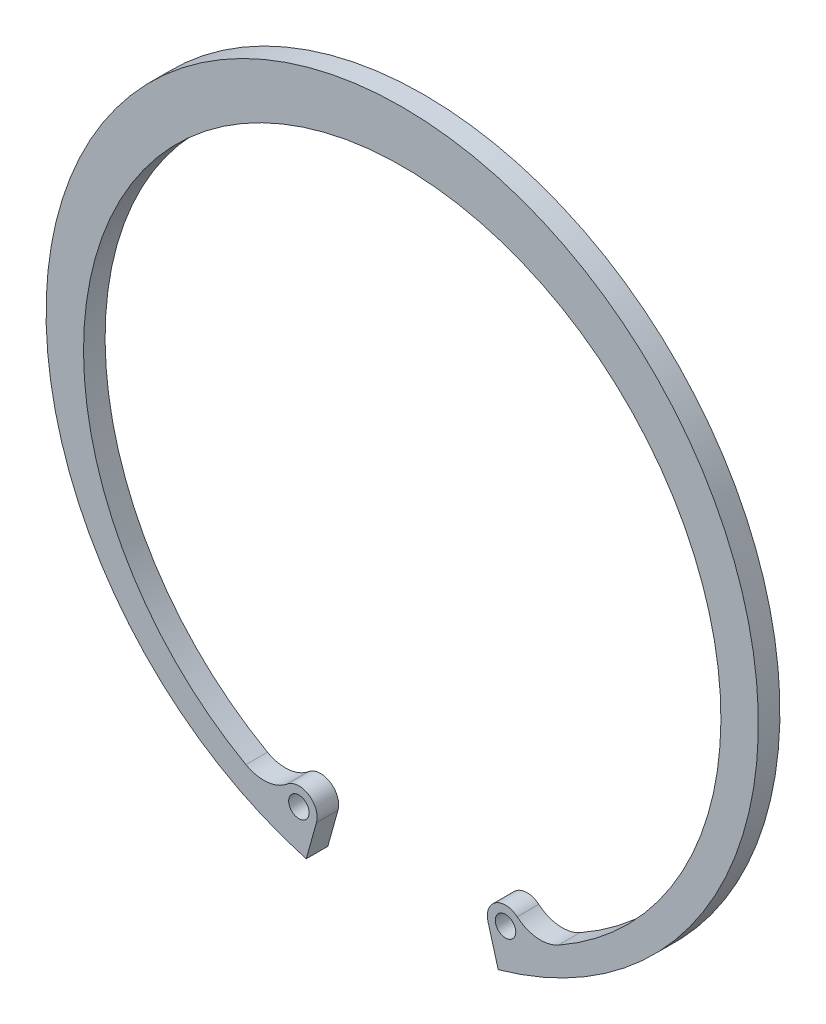
SolidWorks part; units mm, degrees
material "Plain Carbon Steel"
ref_plane "Front Plane" through (0, 0, 0) normal (0, 0, 1) x (1, 0, 0)
ref_plane "Top Plane" through (0, 0, 0) normal (0, 1, 0) x (1, 0, 0)
ref_plane "Right Plane" through (0, 0, 0) normal (1, 0, 0) x (0, 0, -1)
sketch "Sketch1" plane through (0, 0, 0) normal (0, 0, 1) x (1, 0, 0)
  line L0 (-1.7433, 0) -> (1.3428, 0) construction
  line L1 (0, 0) -> (0, 56.55) construction
  line L2 (17.802, -63.6058) -> (15.9096, -56.8442)
  line L3 (-17.802, -63.6058) -> (-15.9096, -56.8442)
  line L4 (0, 0) -> (31.0606, -58.291) construction
  line L5 (0, 0) -> (-31.0606, -58.291) construction
  line L6 (-18.6476, -54.1049) -> (-19.6718, -57.7642) construction
  line L7 (19.204, -56.0931) -> (19.1153, -55.776) construction
  arc A0 (-15.9096, -56.8442) -> (-21.3316, -53.3512) centre (-19.1597, -55.9345) ccw
  arc A1 (21.3316, -53.3512) -> (15.9096, -56.8442) centre (19.1597, -55.9345) ccw
  arc A2 (28.8504, -54.1431) -> (-28.8504, -54.1431) centre (0, -2.5563) ccw construction
  arc A3 (17.802, -63.6058) -> (-17.802, -63.6058) centre (0, 0) ccw
  circle A4 centre (19.1597, -55.9345) radius 1.9
  circle A5 centre (-19.1597, -55.9345) radius 1.9
  arc A6 (28.9856, -54.0673) -> (-28.9856, -54.0673) centre (0, -2.5563) ccw
  arc A7 (-19.1597, -55.9345) -> (19.1597, -55.9345) centre (0, 0) ccw construction
  arc A8 (-28.9856, -54.0673) -> (-21.3316, -53.3512) centre (-25.6754, -48.1847) ccw
  arc A9 (21.3316, -53.3512) -> (28.9856, -54.0673) centre (25.6754, -48.1847) ccw
  dimension "D4" = 59.125
  dimension "D5" = 132.1
  dimension "D7" = 3.375
  dimension "D8" = 3.8
  dimension "D9" = 6.75
  dimension "D1" = 56.55
  dimension "D2" = 61.35
  dimension "D3" = 56.102
  dimension "D6" = 31.272
extrude "Boss-Extrude1" add sketch "Sketch1" along normal blind 4
